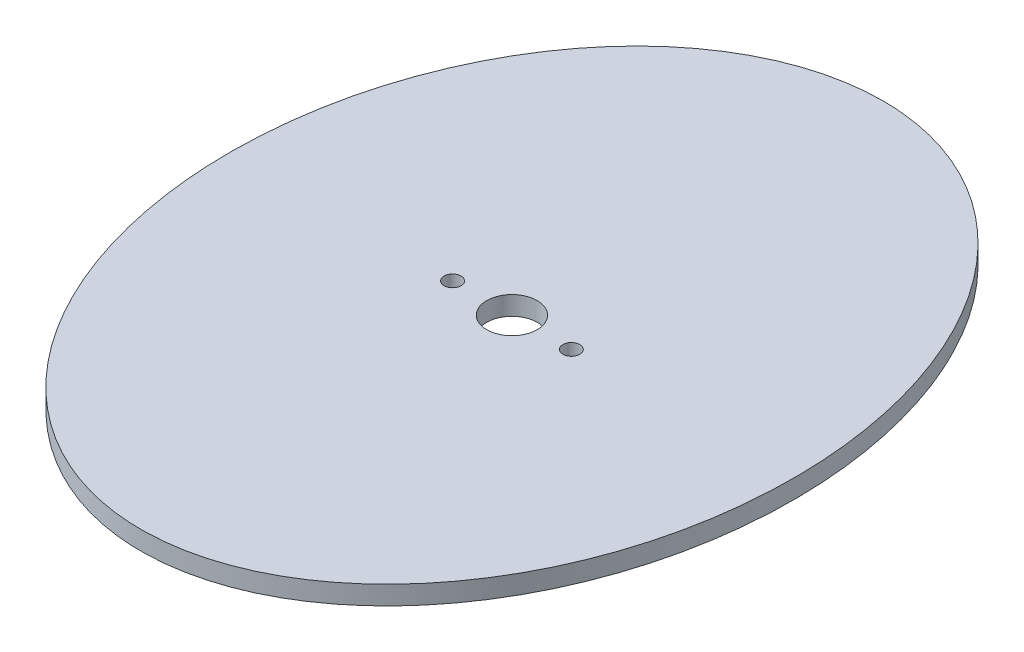
SolidWorks part; units mm, degrees
ref_plane "Front Plane" through (0, 0, 0) normal (0, 0, 1) x (1, 0, 0)
ref_plane "Top Plane" through (0, 0, 0) normal (0, 1, 0) x (1, 0, 0)
ref_plane "Right Plane" through (0, 0, 0) normal (1, 0, 0) x (0, 0, -1)
sketch "Sketch1" plane through (0, 0, 0) normal (0, 1, 0) x (1, 0, 0)
  line L0 (-47.5, 0) -> (47.5, 0) construction
  line L2 (0, 62.5) -> (0, -62.5) construction
  ellipse E0 centre (0, 0) end of major axis (0, 62.5) minor radius 47.5
  dimension "D1" = 95
  dimension "D2" = 125
extrude "Boss-Extrude1" add sketch "Sketch1" along normal blind 3.175
sketch "Sketch2" plane through (0, 3.175, 0) normal (0, 1, 0) x (1, 0, 0)
  line L0 (-10, 0) -> (10, 0) construction
  circle A0 centre (0, 0) radius 4.25
  circle A1 centre (-10, 0) radius 1.425
  circle A2 centre (10, 0) radius 1.425
  point P7 (0, 0)
  dimension "D1" = 8.5
  dimension "D2" = 2.85
  dimension "D3" = 20
extrude "Cut-Extrude1" cut sketch "Sketch2" against normal through all
